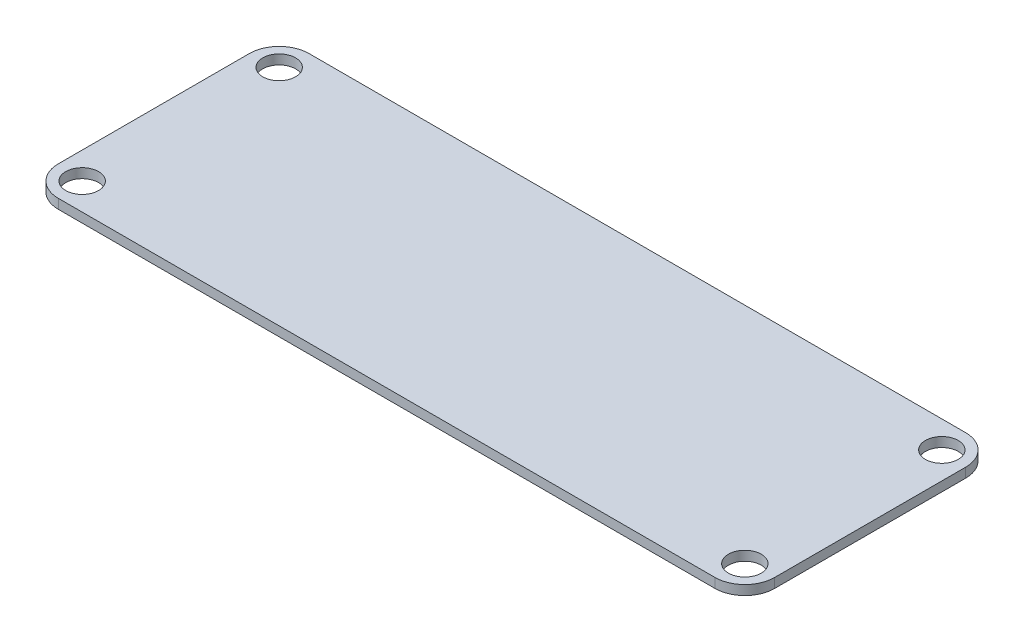
SolidWorks part; units mm, degrees
ref_plane "Ebene vorne" through (0, 0, 0) normal (0, 0, 1) x (1, 0, 0)
ref_plane "Ebene oben" through (0, 0, 0) normal (0, 1, 0) x (1, 0, 0)
ref_plane "Ebene rechts" through (0, 0, 0) normal (1, 0, 0) x (0, 0, -1)
sketch "Skizze1" plane through (0, 0, 0) normal (0, 1, 0) x (1, 0, 0)
  line L1 (-55, 21) -> (55, 21)
  line L2 (-60, 16) -> (-60, -16)
  line L3 (-55, -21) -> (55, -21)
  line L4 (60, 16) -> (60, -16)
  line L5 (-60, 21) -> (60, -21) construction
  line L6 (-60, -21) -> (60, 21) construction
  arc A0 (-60, -16) -> (-55, -21) centre (-55, -16) ccw
  arc A1 (55, -21) -> (60, -16) centre (55, -16) ccw
  arc A2 (55, 21) -> (60, 16) centre (55, 16) cw
  arc A3 (-55, 21) -> (-60, 16) centre (-55, 16) ccw
  point P0 (0, 0)
  dimension "D3" = 5
  dimension "D1" = 120
  dimension "D2" = 42
extrude "Aufsatz-Linear austragen1" add sketch "Skizze1" along normal blind 1.6
sketch "Skizze2" plane through (0, 1.6, 0) normal (0, 1, 0) x (1, 0, 0)
  line L0 (-60, 16) -> (-60, -16) construction
  line L1 (55, 21) -> (-55, 21) construction
  line L2 (-55, -21) -> (55, -21) construction
  line L3 (60, -16) -> (60, 16) construction
  circle A0 centre (-55.5, 16.5) radius 2.75
  circle A1 centre (-55.5, -16.5) radius 2.75
  circle A2 centre (55.5, 16.5) radius 2.75
  circle A3 centre (55.5, -16.5) radius 2.75
  dimension "D1" = 5.5
  dimension "D5" = 4.5
  dimension "D2" = 4.5
  dimension "D3" = 4.5
  dimension "D4" = 4.5
extrude "Schnitt-Linear austragen1" cut sketch "Skizze2" against normal through all
